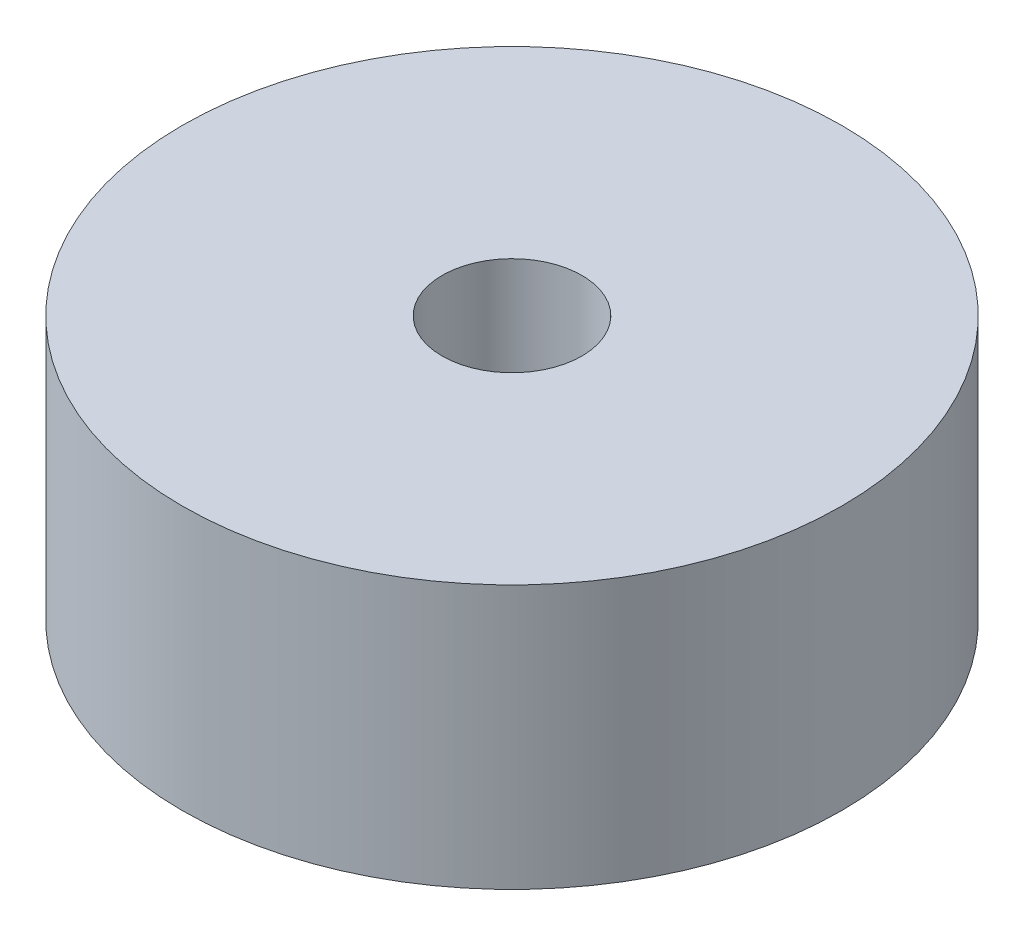
SolidWorks part; units mm, degrees
ref_plane "Front Plane" through (0, 0, 0) normal (0, 0, 1) x (1, 0, 0)
ref_plane "Top Plane" through (0, 0, 0) normal (0, 1, 0) x (1, 0, 0)
ref_plane "Right Plane" through (0, 0, 0) normal (1, 0, 0) x (0, 0, -1)
sketch "Sketch1" plane through (0, 0, 0) normal (0, 1, 0) x (1, 0, 0)
  circle A0 centre (0, 0) radius 9.525
  dimension "D1" = 19.05
extrude "Stock" add sketch "Sketch1" along normal blind 7.62
sketch "Bolt Hole Pattern" plane through (0, 7.62, 0) normal (0, 1, 0) x (1, 0, 0)
  point P0 (0, 0)
hole_wizard "Alignment Pin Hole" positions "Sketch3" profile "Sketch4" tap size "#10-32" standard "ANSI Inch" end condition through all
sketch "Sketch3" plane through (0, 7.62, 0) normal (0, 1, 0) x (1, 0, 0)
  point P0 (0, 0)
sketch "Sketch4" plane through (0, 7.62, 0) normal (1, 0, 0) x (0, 0, 1)
  line L0 (0, 0) -> (0, 7.62)
  line L1 (0, 7.62) -> (2.0193, 7.62)
  line L2 (2.0193, 7.62) -> (2.0193, 0)
  line L5 (2.0193, 0) -> (0, 0)
  line L11 (0, -6.35) -> (0, 107.95) construction
  dimension "Thru Tap Drill Dia." = 4.0386
  dimension "Thru Tap Drill Depth" = 7.62
cosmetic thread "Hole Thread1"
